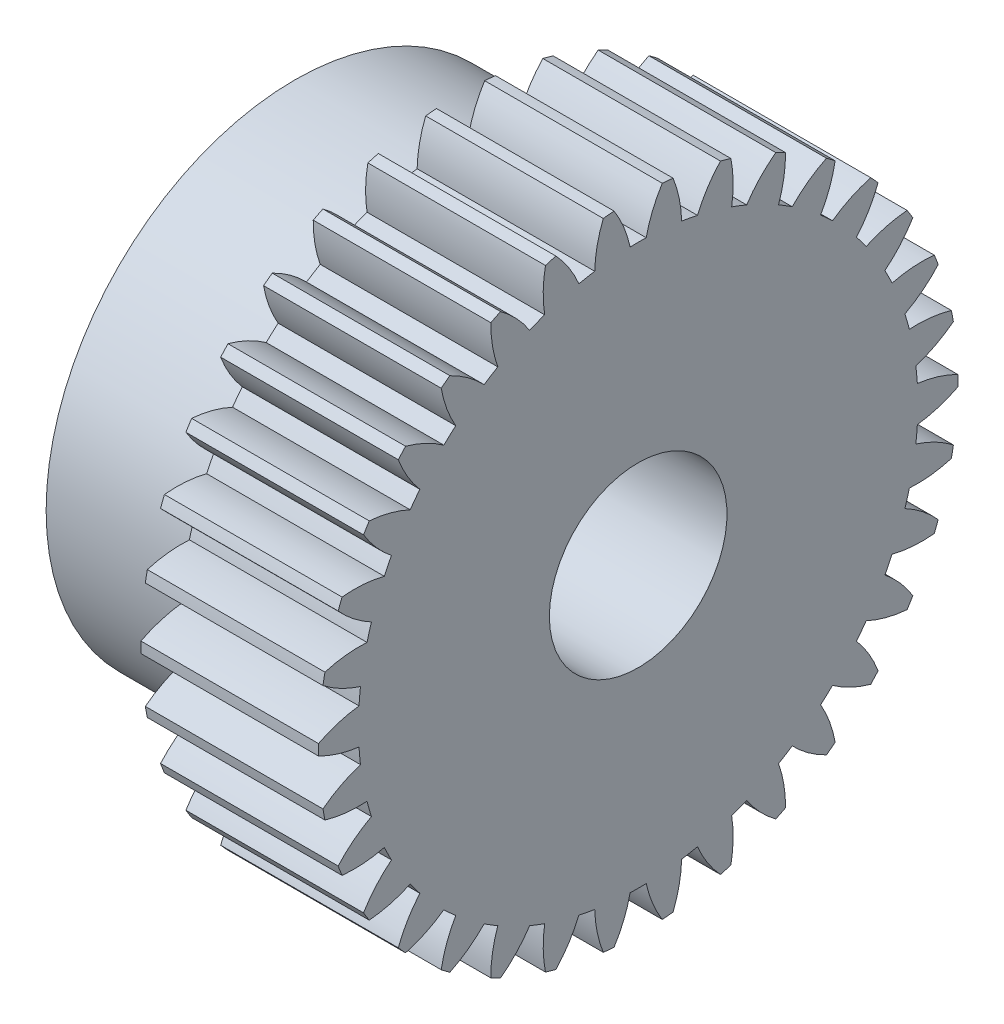
SolidWorks part; units mm, degrees
ref_plane "Plane1" through (0, 0, 0) normal (0, 0, 1) x (1, 0, 0)
ref_plane "Plane2" through (0, 0, 0) normal (0, 1, 0) x (1, 0, 0)
ref_plane "Plane3" through (0, 0, 0) normal (1, 0, 0) x (0, 0, -1)
other "Configuration Table"
sketch "HoldingSke" plane through (0, 0, 0) normal (0, 1, 0) x (1, 0, 0)
  line L0 (0, 0) -> (0.5527, -0.3728)
  line L1 (-15, 0) -> (100, 0) construction
  line L2 (0, 0) -> (-2.1039, 2.3779)
  line L3 (0, 0) -> (-11.863, 4.5341)
  line L4 (0, 0) -> (7.1596, 4.8292)
  line L5 (0, 0) -> (-27.1716, -10.1342)
  line L6 (0, 0) -> (-12.4344, -8.3896)
  line L7 (-2.1039, 2.3779) -> (4.1384, 30.6981)
  line L8 (-76.2, 54.61) -> (-73.9, 54.61)
  line L9 (-71.009, 38.7566) -> (-53.1078, 45.2721)
  line L10 (-76.2, 71.12) -> (104.1128, 71.12)
  line L11 (0, 0) -> (-15, 0)
  line L12 (-76.2, 101.6) -> (-76.147, 101.6)
  line L13 (24.9733, 27.94) -> (52.9518, 28.4284)
  line L14 (24.9733, 27.94) -> (24.9743, 27.94)
  line L15 (24.9733, 27.94) -> (100.4006, 29.5858)
  line L16 (-63.627, -1.5) -> (-12.827, -1.5)
  circle A0 centre (0, 0) radius 7.5
  circle A1 centre (0, 0) radius 21
  circle A2 centre (0, 0) radius 21
  circle A3 centre (0, 0) radius 7.5
  dimension "MHD" = 42
  dimension "Hub_dia" = 42
  dimension "Bore" = 15
  dimension "MBD" = 15
  dimension "Num_teeth" = 34
  dimension "Pitch" = 0.6667
  dimension "Overall_len" = 29
  dimension "Show_teeth" = 34
  dimension "Thickness" = 15
  dimension "OAL" = 29.0001
  dimension "T_dim" = 2.3
  dimension "Ap" = 20
  dimension "H" = 19.05
  dimension "Pitch_radius" = 180.3128
  dimension "Width" = 15
  dimension "Backlash" = 0.053
  dimension "Addendum_fac" = 1
  dimension "Dedendum_fac" = 1.25
  dimension "Clearance_fac" = 0.25
  dimension "Dedendum_add" = 0.001
  dimension "Module" = 1.5
sketch "BasProSke" plane through (0, 0, 0) normal (0, 1, 0) x (1, 0, 0)
  line L0 (-10, 0) -> (60, 0) construction
  line L1 (0, 0) -> (0, 27)
  line L2 (0, 0) -> (15, 0)
  line L3 (15, 0) -> (15, 27)
  line L4 (15, 27) -> (0, 27)
  dimension "Thickness" = 15
  dimension "Diameter" = 54
revolve "Base-Revolve" add sketch "BasProSke" angle 360 about L0
sketch "TooCutSke" plane through (0, 0, 0) normal (1, 0, 0) x (0, 0, -1)
  line L1 (0, 0) -> (0, 107) construction
  line L2 (0, 0) -> (-1.2704, 25.4683) construction
  line L3 (0, 0) -> (-4.7014, 50.7365) construction
  line L4 (-1.2704, 25.4683) -> (-2.3507, 25.3682) construction
  arc A0 (0.6808, 23.6142) -> (-0.6808, 23.6142) centre (0, 0) ccw
  arc A1 (2.0508, 26.9475) -> (-2.0508, 26.9475) centre (0, 0) ccw
  circle A2 centre (0, 0) radius 25.5 construction
  circle A3 centre (0, 0) radius 23.9622 construction
  arc A4 (-0.6808, 23.6142) -> (-2.0508, 26.9475) centre (-10.6517, 21.4645) ccw
  arc A5 (2.0508, 26.9475) -> (0.6808, 23.6142) centre (10.6517, 21.4645) ccw
  dimension "Root_dia" = 47.248
  dimension "Overcut_dia" = 54.0508
  dimension "Pitch_dia" = 51
  dimension "Base_dia" = 47.9243
  dimension "Flank_rad" = 10.2
  dimension "Half_ang" = 5.294
  dimension "Half_CT" = 1.0849
extrude "ToothCut" cut sketch "TooCutSke" along normal through all
fillet "Breaks" [suppressed] radius 0.03
fillet "RootFillets" [suppressed] radius 0.376
pattern_circular "TeethCuts" count 34 every 10.588 about axis through (-10, 0, 0) along (1, 0, 0) of "ToothCut", "RootFillets", "Breaks"
sketch "HubNeaOneSke" plane through (0, 0, 0) normal (-1, 0, 0) x (0, 0, 1)
  circle A0 centre (0, 0) radius 21
  dimension "Diameter" = 42
extrude "HubNearOne" add sketch "HubNeaOneSke" along normal blind 14.0001
sketch "HubNeaBotSke" plane through (0, 0, 0) normal (-1, 0, 0) x (0, 0, 1)
  circle A0 centre (0, 0) radius 21
  dimension "Diameter" = 42
extrude "HubNearBoth" [suppressed] add sketch "HubNeaBotSke" along normal blind 7
ref_plane "FarPln" through (15, 0, 0) normal (1, 0, 0) x (0, 0, -1)
sketch "HubFarSke" plane through (15, 0, 0) normal (1, 0, 0) x (0, 0, -1)
  circle A0 centre (0, 0) radius 21
  dimension "Diameter" = 42
extrude "HubFar" [suppressed] add sketch "HubFarSke" along normal blind 7
sketch "BorSke" plane through (0, 0, 0) normal (1, 0, 0) x (0, 0, -1)
  circle A0 centre (0, 0) radius 7.5
  dimension "Diameter" = 15
extrude "Bore" cut sketch "BorSke" along normal mid plane 58.0001
sketch "KeySke" plane through (0, 0, 0) normal (1, 0, 0) x (0, 0, -1)
  line L0 (-2.5, 0) -> (-2.5, 9.8)
  line L1 (-2.5, 9.8) -> (2.5, 9.8)
  line L2 (2.5, 9.8) -> (2.5, 0)
  line L3 (0, 0) -> (0, 34) construction
  line L4 (-2.5, 0) -> (2.5, 0)
  dimension "Offset" = 9.8
  dimension "Width" = 5
extrude "Keyway" [suppressed] cut sketch "KeySke" along normal mid plane 58.0001
pattern_circular "Keyway2" [suppressed] count 2 every 90 about axis through (-10, 0, 0) along (1, 0, 0)
sketch "Sketch1" plane through (-14.0001, 0, 0) normal (-1, 0, 0) x (0, 0, 1)
  line L0 (0, 0) -> (27, 0)
  arc A0 (26.9961, -0.4575) -> (26.9961, 0.4575) centre (0, 0) ccw construction
equation "' \"Module@HoldingSke\" = 6.35"
equation "' \"Num_teeth@HoldingSke\" = 12"
equation "' \"Ap@HoldingSke\" =  20"
equation "' \"Ap@HoldingSke\" = 20"
equation "' \"Width@HoldingSke\" = 0.5 * 25.4"
equation "' \"Hub_dia@HoldingSke\"= 1 * 25.4"
equation "' \"Hub_dia@HoldingSke\" = 1 * 25.4"
equation "' \"Overall_len@HoldingSke\" = 1.0 * 25.4"
equation "' \"Bore@HoldingSke\" = 0.75 * 25.4"
equation "' \"T_dim@HoldingSke\" = 0.1 * 25.4"
equation "' \"Width@KeySke\" = 0.25 * 25.4"
equation "' \"Show_teeth@HoldingSke\" = 13"
equation "' \"Backlash@HoldingSke\" = 0.009 * 25.4"
equation "' \"Addendum_fac@HoldingSke\" = 1.0"
equation "' \"Dedendum_fac@HoldingSke\" = 1.25"
equation "' \"Dedendum_add@HoldingSke\" = 0.00005 * 25.4"
equation "' \"Clearance_fac@HoldingSke\" = 0.25"
equation "\"Pitch@HoldingSke\" = 1 / \"Module@HoldingSke\""
equation "\"Overcut_dia@TooCutSke\" = (\"Num_teeth@HoldingSke\" + 2 * \"Addendum_fac@HoldingSke\") / \"Pitch@HoldingSke\" + 0.002 * 25.4"
equation "\"Pitch_dia@TooCutSke\" = \"Num_teeth@HoldingSke\" / \"Pitch@HoldingSke\""
equation "\"Base_dia@TooCutSke\" = \"Num_teeth@HoldingSke\" / \"Pitch@HoldingSke\" * cos((\"Ap@HoldingSke\"  * 3.14159265 / 180))"
equation "\"Root_dia@TooCutSke\" = (\"Num_teeth@HoldingSke\" + 2) / \"Pitch@HoldingSke\" - 2 * (\"Addendum_fac@HoldingSke\" + \"Dedendum_fac@HoldingSke\") / \"Pitch@HoldingSke\" - \"Dedendum_add@HoldingSke\" * 2"
equation "\"Half_ang@TooCutSke\" = 180 / \"Num_teeth@HoldingSke\""
equation "\"Half_CT@TooCutSke\" = \"Num_teeth@HoldingSke\" / \"Pitch@HoldingSke\" * sin((3.14159265 / 2 / \"Num_teeth@HoldingSke\")) / 2 - 7 * \"Backlash@HoldingSke\" / 4"
equation "\"Flank_rad@TooCutSke\" = \"Num_teeth@HoldingSke\" / \"Pitch@HoldingSke\" / 5"
equation "\"Radius@RootFillets\" = \"Clearance_fac@HoldingSke\" / \"Pitch@HoldingSke\" + \"Dedendum_add@HoldingSke\""
equation "\"Break_rad@Breaks\" = 0.02 / \"Pitch@HoldingSke\""
equation "\"Thickness@HoldingSke\" = \"Width@HoldingSke\""
equation "\"OAL@HoldingSke\" = \"Thickness@HoldingSke\""
equation "\"MHD@HoldingSke\" = (\"Num_teeth@HoldingSke\" + 2) / \"Pitch@HoldingSke\" - 2 * (\"Addendum_fac@HoldingSke\" + \"Dedendum_fac@HoldingSke\")  / \"Pitch@HoldingSke\" - \"Dedendum_add@HoldingSke\" * 2"
equation "\"MBD@HoldingSke\" = (\"Num_teeth@HoldingSke\" + 2) / \"Pitch@HoldingSke\" - 2 * (\"Addendum_fac@HoldingSke\" + \"Dedendum_fac@HoldingSke\")  / \"Pitch@HoldingSke\" - \"Dedendum_add@HoldingSke\" * 2 - 0.002 * 25.4"
equation "\"MHD@HoldingSke\" = ((sgn( \"MHD@HoldingSke\" - \"Hub_dia@HoldingSke\" )-1)*( \"MHD@HoldingSke\" - \"Hub_dia@HoldingSke\" ))/-2+ \"Hub_dia@HoldingSke\""
equation "\"MBD@HoldingSke\" = ((sgn( \"MBD@HoldingSke\" - \"Bore@HoldingSke\" )-1)*( \"MBD@HoldingSke\" - \"Bore@HoldingSke\" ))/-2+ \"Bore@HoldingSke\""
equation "\"OAL@HoldingSke\" = ((sgn( \"OAL@HoldingSke\" - \"Overall_len@HoldingSke\" )+1)*( \"OAL@HoldingSke\" - \"Overall_len@HoldingSke\" ))/2 + \"Overall_len@HoldingSke\" + 0.000002 * 25.4"
equation "\"Num_teeth@TeethCuts\" = int( \"Show_teeth@HoldingSke\" ) + 1"
equation "\"Num_teeth@TeethCuts\" = ((sgn( \"Num_teeth@TeethCuts\" - \"Num_teeth@HoldingSke\" )-1)*( \"Num_teeth@TeethCuts\" - \"Num_teeth@HoldingSke\" ))/-2+ \"Num_teeth@HoldingSke\""
equation "\"Num_teeth@TeethCuts\" = ((sgn( \"Num_teeth@TeethCuts\" - 2.0)+1)*( \"Num_teeth@TeethCuts\" - 2.0))/2 +2.0"
equation "\"Angle@TeethCuts\" = 360.0 / \"Num_teeth@HoldingSke\""
equation "\"Diameter@BasProSke\" = (\"Num_teeth@HoldingSke\" + 2 * \"Addendum_fac@HoldingSke\") / \"Pitch@HoldingSke\""
equation "\"Thickness@BasProSke\"  = \"Thickness@HoldingSke\""
equation "' \"Fillet_rad@BasProSke\" =  \"Thickness@HoldingSke\" * 0.05"
equation "' \"Fillet_rad@BasProSke\" = \"Thickness@HoldingSke\" * 0.05"
equation "\"MHD@HoldingSke\" = ((sgn( \"MHD@HoldingSke\" - \"Root_dia@TooCutSke\" )-1)*( \"MHD@HoldingSke\" - \"Root_dia@TooCutSke\" ))/-2+ \"Root_dia@TooCutSke\""
equation "\"Diameter@HubNeaOneSke\" = \"MHD@HoldingSke\""
equation "\"Length@HubNearOne\" = \"OAL@HoldingSke\" - \"Thickness@BasProSke\""
equation "\"Diameter@HubNeaBotSke\" = \"MHD@HoldingSke\""
equation "\"Length@HubNearBoth\" = ( \"OAL@HoldingSke\" - \"Thickness@BasProSke\" ) / 2.0"
equation "\"Thickness@FarPln\" = \"Thickness@BasProSke\""
equation "\"Diameter@HubFarSke\" = \"MHD@HoldingSke\""
equation "\"Length@HubFar\" = ( \"OAL@HoldingSke\" - \"Thickness@BasProSke\" ) / 2.0"
equation "\"Diameter@BorSke\" = \"MBD@HoldingSke\""
equation "\"D1@Bore\" = \"OAL@HoldingSke\" * 2.0"
equation "\"D1@Keyway\" = \"OAL@HoldingSke\" * 2.0"
equation "\"Offset@KeySke\" = \"T_dim@HoldingSke\" + \"MBD@HoldingSke\" / 2.0"
